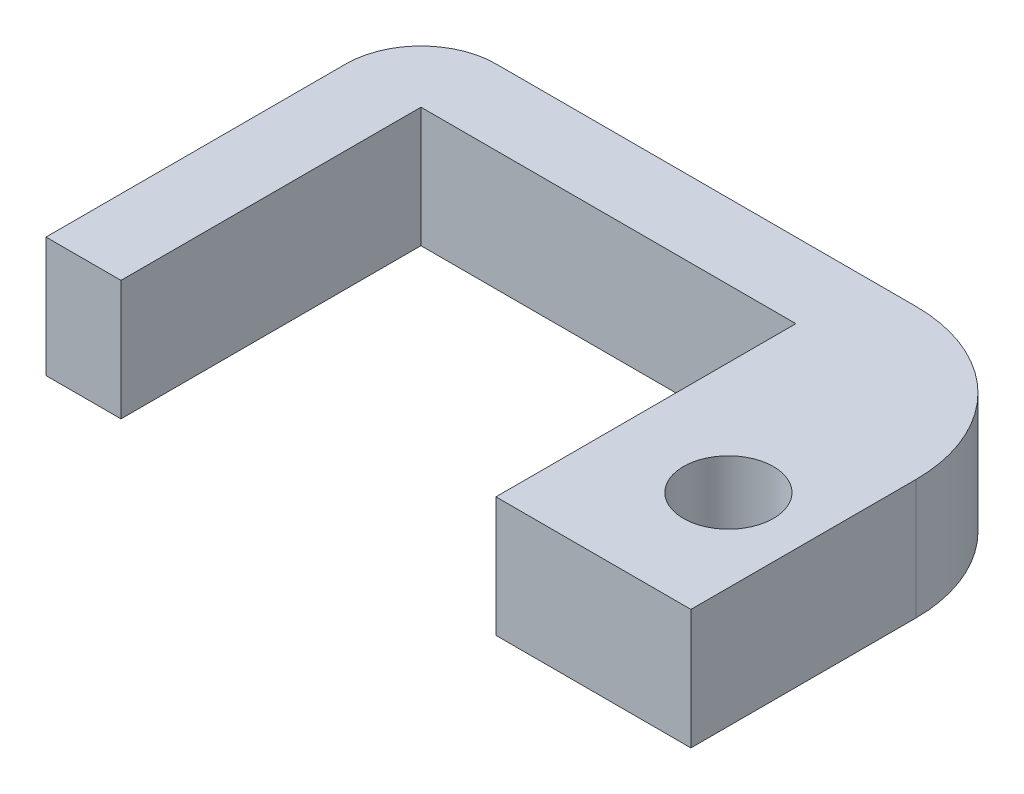
SolidWorks part; units mm, degrees
ref_plane "Alzado" through (0, 0, 0) normal (0, 0, 1) x (1, 0, 0)
ref_plane "Planta" through (0, 0, 0) normal (0, 1, 0) x (1, 0, 0)
ref_plane "Vista lateral" through (0, 0, 0) normal (1, 0, 0) x (0, 0, -1)
sketch "Croquis1" plane through (0, 0, 0) normal (0, 1, 0) x (1, 0, 0)
  line L0 (25, 0) -> (38, 0)
  line L2 (0, 0) -> (0, 20)
  line L3 (0, 20) -> (25, 20)
  line L4 (25, 0) -> (25, 20)
  line L5 (38, 0) -> (38, 15)
  line L6 (28, 25) -> (0, 25)
  line L7 (-5, 20) -> (-5, 0)
  line L8 (-5, 0) -> (0, 0)
  circle A0 centre (32.5, 8) radius 2
  arc A1 (28, 25) -> (38, 15) centre (28, 15) cw
  arc A2 (-5, 20) -> (0, 25) centre (0, 20) cw
  point P5 (12.5, 8)
  point P11 (12.5, 20)
  dimension "D4" = 4
  dimension "D9" = 10
  dimension "D10" = 5
  dimension "D1" = 25
  dimension "D2" = 20
  dimension "D3" = 12
  dimension "D5" = 13
  dimension "D6" = 20
  dimension "D7" = 5
  dimension "D8" = 5
extrude "Saliente-Extruir1" add sketch "Croquis1" along normal blind 8
sketch "Croquis2" plane through (0, 0, 0) normal (0, -1, 0) x (1, 0, 0)
  circle A0 centre (32.5, -8) radius 3
  dimension "D1" = 6
extrude "Cortar-Extruir1" cut sketch "Croquis2" against normal blind 9
